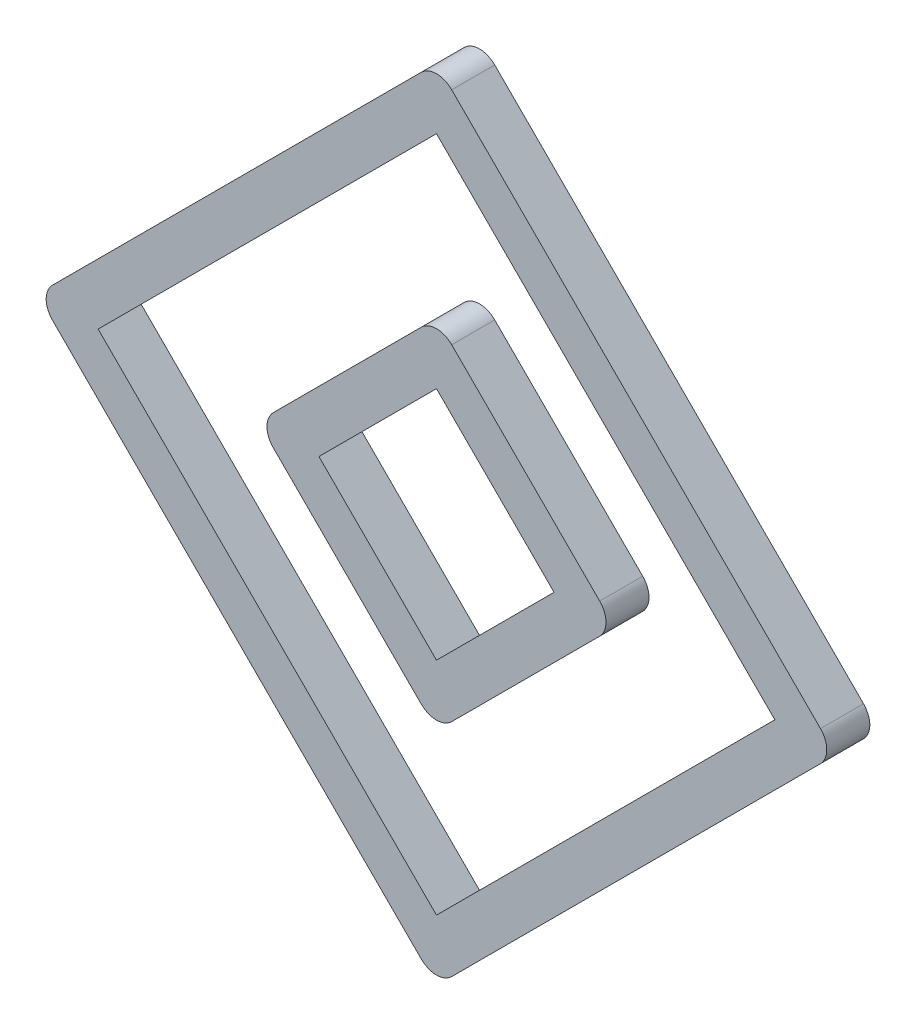
SolidWorks part; units mm, degrees
ref_plane "Front Plane" through (0, 0, 0) normal (0, 0, 1) x (1, 0, 0)
ref_plane "Top Plane" through (0, 0, 0) normal (0, 1, 0) x (1, 0, 0)
ref_plane "Right Plane" through (0, 0, 0) normal (1, 0, 0) x (0, 0, -1)
sketch "Sketch2" plane through (0, 0, 0) normal (0, 0, 1) x (1, 0, 0)
  line L34 (-37.3762, -135.6526) -> (-22.3762, -120.6526)
  line L35 (-23.6137, -119.4151) -> (-38.6137, -134.4151)
  line L36 (-37.3762, -135.6526) -> (-22.3762, -120.6526)
  line L37 (-23.6137, -119.4151) -> (-38.6137, -134.4151)
  line L38 (-28.396, -135.6526) -> (-22.3762, -129.6328)
  line L39 (-23.6137, -128.3954) -> (-29.6334, -134.4151)
  line L40 (-28.396, -135.6526) -> (-22.3762, -129.6328)
  line L41 (-23.6137, -128.3954) -> (-29.6334, -134.4151)
  line L42 (-22.3762, -140.4349) -> (-28.396, -134.4151)
  line L43 (-29.6334, -135.6526) -> (-23.6137, -141.6723)
  line L44 (-22.3762, -140.4349) -> (-28.396, -134.4151)
  line L45 (-29.6334, -135.6526) -> (-23.6137, -141.6723)
  line L46 (-22.3762, -141.6723) -> (-16.3565, -135.6526)
  line L47 (-17.5939, -134.4151) -> (-23.6137, -140.4349)
  line L48 (-22.3762, -141.6723) -> (-16.3565, -135.6526)
  line L49 (-17.5939, -134.4151) -> (-23.6137, -140.4349)
  line L50 (-8.6137, -134.4151) -> (-23.6137, -149.4151)
  line L51 (-22.3762, -150.6526) -> (-7.3762, -135.6526)
  line L52 (-8.6137, -134.4151) -> (-23.6137, -149.4151)
  line L53 (-22.3762, -150.6526) -> (-7.3762, -135.6526)
  line L54 (-38.6137, -135.6526) -> (-23.6137, -150.6526)
  line L55 (-22.3762, -149.4151) -> (-37.3762, -134.4151)
  line L56 (-38.6137, -135.6526) -> (-23.6137, -150.6526)
  line L57 (-22.3762, -149.4151) -> (-37.3762, -134.4151)
  line L58 (-23.6137, -120.6526) -> (-8.6137, -135.6526)
  line L59 (-7.3762, -134.4151) -> (-22.3762, -119.4151)
  line L60 (-23.6137, -120.6526) -> (-8.6137, -135.6526)
  line L61 (-7.3762, -134.4151) -> (-22.3762, -119.4151)
  line L62 (-16.3565, -134.4151) -> (-22.3762, -128.3954)
  line L63 (-23.6137, -129.6328) -> (-17.5939, -135.6526)
  line L64 (-16.3565, -134.4151) -> (-22.3762, -128.3954)
  line L65 (-23.6137, -129.6328) -> (-17.5939, -135.6526)
  arc A18 (-38.6137, -134.4151) -> (-37.3762, -135.6526) centre (-37.995, -135.0339) ccw
  arc A19 (-22.3762, -120.6526) -> (-23.6137, -119.4151) centre (-22.995, -120.0339) ccw
  arc A20 (-38.6137, -134.4151) -> (-37.3762, -135.6526) centre (-37.995, -135.0339) ccw
  arc A21 (-22.3762, -120.6526) -> (-23.6137, -119.4151) centre (-22.995, -120.0339) ccw
  arc A22 (-22.3762, -129.6328) -> (-23.6137, -128.3954) centre (-22.995, -129.0141) ccw
  arc A23 (-29.6334, -134.4151) -> (-28.396, -135.6526) centre (-29.0147, -135.0339) ccw
  arc A24 (-22.3762, -129.6328) -> (-23.6137, -128.3954) centre (-22.995, -129.0141) ccw
  arc A25 (-29.6334, -134.4151) -> (-28.396, -135.6526) centre (-29.0147, -135.0339) ccw
  arc A26 (-23.6137, -141.6723) -> (-22.3762, -140.4349) centre (-22.995, -141.0536) ccw
  arc A27 (-28.396, -134.4151) -> (-29.6334, -135.6526) centre (-29.0147, -135.0339) ccw
  arc A28 (-23.6137, -141.6723) -> (-22.3762, -140.4349) centre (-22.995, -141.0536) ccw
  arc A29 (-28.396, -134.4151) -> (-29.6334, -135.6526) centre (-29.0147, -135.0339) ccw
  arc A30 (-23.6137, -140.4349) -> (-22.3762, -141.6723) centre (-22.995, -141.0536) ccw
  arc A31 (-16.3565, -135.6526) -> (-17.5939, -134.4151) centre (-16.9752, -135.0339) ccw
  arc A32 (-23.6137, -140.4349) -> (-22.3762, -141.6723) centre (-22.995, -141.0536) ccw
  arc A33 (-16.3565, -135.6526) -> (-17.5939, -134.4151) centre (-16.9752, -135.0339) ccw
  arc A34 (-7.3762, -135.6526) -> (-8.6137, -134.4151) centre (-7.995, -135.0339) ccw
  arc A35 (-23.6137, -149.4151) -> (-22.3762, -150.6526) centre (-22.995, -150.0339) ccw
  arc A36 (-7.3762, -135.6526) -> (-8.6137, -134.4151) centre (-7.995, -135.0339) ccw
  arc A37 (-23.6137, -149.4151) -> (-22.3762, -150.6526) centre (-22.995, -150.0339) ccw
  arc A38 (-37.3762, -134.4151) -> (-38.6137, -135.6526) centre (-37.995, -135.0339) ccw
  arc A39 (-23.6137, -150.6526) -> (-22.3762, -149.4151) centre (-22.995, -150.0339) ccw
  arc A40 (-37.3762, -134.4151) -> (-38.6137, -135.6526) centre (-37.995, -135.0339) ccw
  arc A41 (-23.6137, -150.6526) -> (-22.3762, -149.4151) centre (-22.995, -150.0339) ccw
  arc A42 (-8.6137, -135.6526) -> (-7.3762, -134.4151) centre (-7.995, -135.0339) ccw
  arc A43 (-22.3762, -119.4151) -> (-23.6137, -120.6526) centre (-22.995, -120.0339) ccw
  arc A44 (-8.6137, -135.6526) -> (-7.3762, -134.4151) centre (-7.995, -135.0339) ccw
  arc A45 (-22.3762, -119.4151) -> (-23.6137, -120.6526) centre (-22.995, -120.0339) ccw
  arc A46 (-22.3762, -128.3954) -> (-23.6137, -129.6328) centre (-22.995, -129.0141) ccw
  arc A47 (-17.5939, -135.6526) -> (-16.3565, -134.4151) centre (-16.9752, -135.0339) ccw
  arc A48 (-22.3762, -128.3954) -> (-23.6137, -129.6328) centre (-22.995, -129.0141) ccw
  arc A49 (-17.5939, -135.6526) -> (-16.3565, -134.4151) centre (-16.9752, -135.0339) ccw
  dimension "D1" = 0
  dimension "D2" = 0
  dimension "D3" = 0
  dimension "D4" = 0
  dimension "D5" = 0
  dimension "D6" = 0
  dimension "D7" = 0
  dimension "D8" = 0
extrude "Boss-Extrude1" add sketch "Sketch2" against normal up to surface (1.75 mm away)
